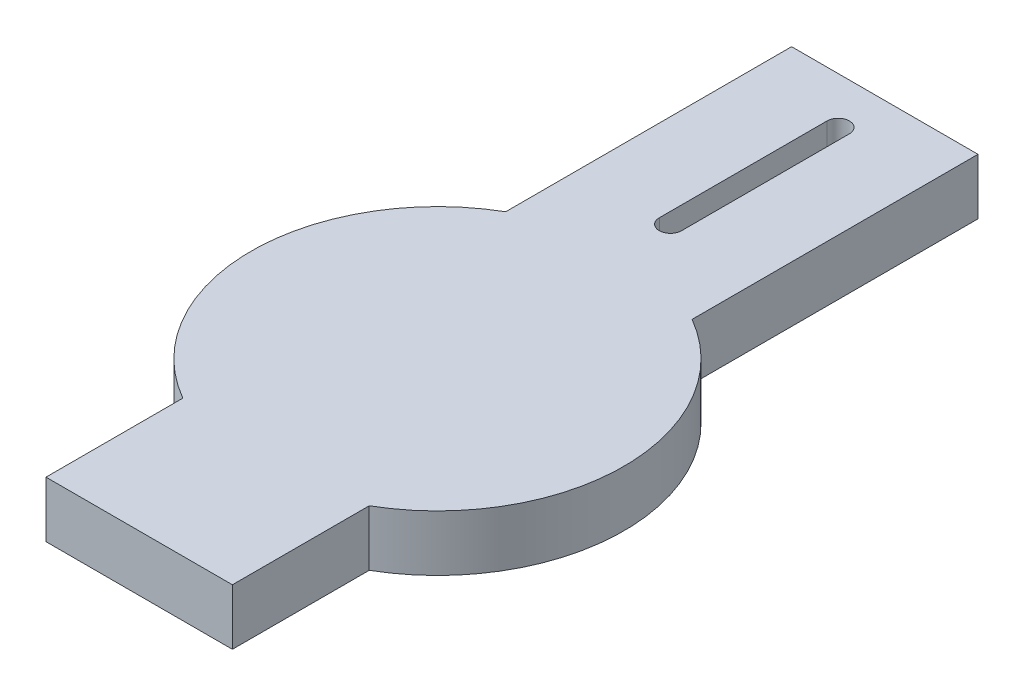
SolidWorks part; units mm, degrees
ref_plane "Front Plane" through (0, 0, 0) normal (0, 0, 1) x (1, 0, 0)
ref_plane "Top Plane" through (0, 0, 0) normal (0, 1, 0) x (1, 0, 0)
ref_plane "Right Plane" through (0, 0, 0) normal (1, 0, 0) x (0, 0, -1)
sketch "Sketch2" plane through (0, 0, 0) normal (0, 1, 0) x (1, 0, 0)
  line L0 (6.35, 10.9985) -> (6.35, 30.48)
  line L2 (-6.35, -20.32) -> (-6.35, -10.9985)
  line L3 (-6.35, 30.48) -> (6.35, 30.48)
  line L4 (6.35, -20.32) -> (6.35, -10.9985)
  line L5 (-3.8279, -18.3741) -> (6.35, 30.48) construction
  line L6 (-6.35, 30.48) -> (3.8279, -18.3741) construction
  line L7 (-6.35, 10.9985) -> (-6.35, 30.48)
  line L8 (-55, 0) -> (55, 0) construction
  line L9 (0, 12.7) -> (0, 30.48) construction
  line L10 (-6.35, -20.32) -> (6.35, -20.32)
  line L11 (0, 27.305) -> (0, 15.875) construction
  line L12 (0, 15.875) -> (0, 27.305) construction
  line L13 (-0.762, 15.875) -> (-0.762, 27.305)
  line L14 (0.762, 15.875) -> (0.762, 27.305)
  arc A0 (-6.35, 10.9985) -> (-6.35, -10.9985) centre (0, 0) ccw
  arc A1 (6.35, -10.9985) -> (6.35, 10.9985) centre (0, 0) ccw
  arc A2 (-6.35, 10.9985) -> (6.35, 10.9985) centre (0, 0) cw construction
  arc A3 (-6.35, -10.9985) -> (6.35, -10.9985) centre (0, 0) ccw construction
  circle A4 centre (0, 27.305) radius 0.762 construction
  circle A5 centre (0, 15.875) radius 0.762 construction
  arc A6 (-0.762, 15.875) -> (0.762, 15.875) centre (0, 15.875) ccw
  arc A7 (0.762, 27.305) -> (-0.762, 27.305) centre (0, 27.305) ccw
  point P17 (0, -12.7)
  point P22 (0, 21.59)
  point P23 (0, 21.59)
  point P24 (0, 21.59)
  dimension "D1" = 25.4
  dimension "D5" = 1.524
  dimension "D6" = 11.43
  dimension "D2" = 12.7
  dimension "D3" = 17.78
  dimension "D4" = 7.62
extrude "Boss-Extrude1" add sketch "Sketch2" along normal blind 3.81
